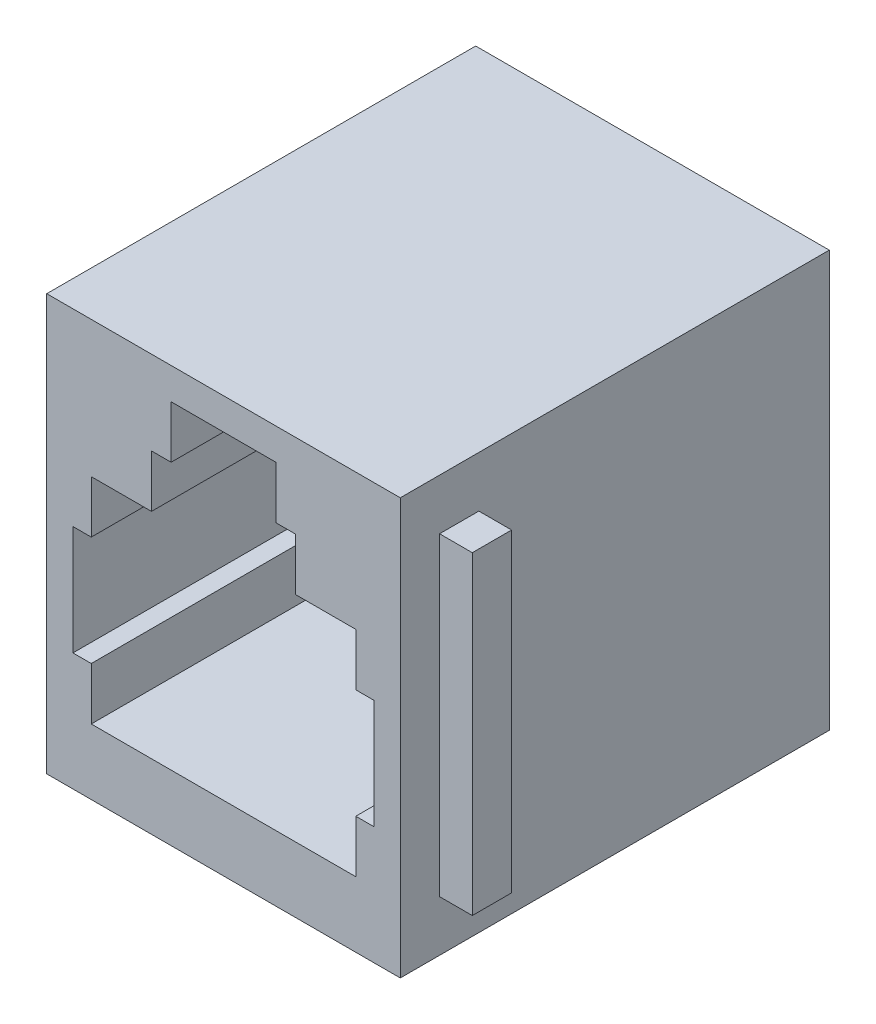
SolidWorks part; units mm, degrees
ref_plane "Front Plane" through (0, 0, 0) normal (0, 0, 1) x (1, 0, 0)
ref_plane "Top Plane" through (0, 0, 0) normal (0, 1, 0) x (1, 0, 0)
ref_plane "Right Plane" through (0, 0, 0) normal (1, 0, 0) x (0, 0, -1)
sketch "Sketch1" plane through (0, 0, 0) normal (0, 0, 1) x (1, 0, 0)
  line L0 (0, 0) -> (0, -7.94) construction
  line L1 (-6.75, 7.94) -> (6.75, 7.94)
  line L2 (-6.75, 7.94) -> (-6.75, -7.94)
  line L3 (-6.75, -7.94) -> (6.75, -7.94)
  line L4 (6.75, 7.94) -> (6.75, -7.94)
  line L5 (0, 0) -> (-6.75, 0) construction
  dimension "D1" = 15.88
  dimension "D2" = 13.5
extrude "Boss-Extrude1" add sketch "Sketch1" along normal blind 16.38
sketch "Sketch2" plane through (0, 0, 16.38) normal (0, 0, 1) x (1, 0, 0)
  line L0 (0, 0) -> (0, 6.74) construction
  line L1 (-2, 6.74) -> (2, 6.74)
  line L2 (2, 6.74) -> (2, 4.74)
  line L3 (2, 4.74) -> (2.75, 4.74)
  line L4 (2.75, 4.74) -> (2.75, 2.74)
  line L5 (2.75, 2.74) -> (5.05, 2.74)
  line L6 (5.05, 2.74) -> (5.05, 0.74)
  line L7 (5.05, 0.74) -> (5.75, 0.74)
  line L8 (5.75, 0.74) -> (5.75, -3.44)
  line L9 (5.75, -3.44) -> (5.05, -3.44)
  line L10 (5.05, -3.44) -> (5.05, -5.44)
  line L11 (5.05, -5.44) -> (-5.05, -5.44)
  line L12 (0, 0) -> (0, -5.44) construction
  line L13 (6.75, -7.94) -> (6.75, 7.94) construction
  line L14 (6.75, 7.94) -> (-6.75, 7.94) construction
  line L15 (-6.75, -7.94) -> (6.75, -7.94) construction
  line L16 (5.05, 0.74) -> (5.05, -3.44) construction
  line L17 (-5.05, -3.44) -> (-5.05, -5.44)
  line L18 (-5.75, -3.44) -> (-5.05, -3.44)
  line L19 (-5.05, 0.74) -> (-5.75, 0.74)
  line L20 (-5.75, 0.74) -> (-5.75, -3.44)
  line L21 (-5.05, 2.74) -> (-5.05, 0.74)
  line L22 (-2.75, 2.74) -> (-5.05, 2.74)
  line L23 (-2.75, 4.74) -> (-2.75, 2.74)
  line L24 (-2, 4.74) -> (-2.75, 4.74)
  line L25 (-2, 6.74) -> (-2, 4.74)
  point P8 (4.7, 1.6169)
  point P21 (4.7, 2.8427)
  point P22 (2.5785, 3.04)
  dimension "D1" = 1
  dimension "D2" = 1.2
  dimension "D3" = 2.5
  dimension "D4" = 2
  dimension "D5" = 0.7
  dimension "D6" = 2
  dimension "D7" = 4
  dimension "D8" = 5.5
extrude "Cut-Extrude1" cut sketch "Sketch2" against normal offset from surface (15.38 mm away) 1 up to face at (0, 0, 0)
sketch "Sketch3" plane through (0, 0, 0) normal (0, 1, 0) x (1, 0, 0)
  line L0 (0, 0) -> (0, -16.38) construction
  line L1 (6.75, -16.38) -> (-6.75, -16.38) construction
  line L2 (6.75, -16.38) -> (6.75, 0) construction
  line L3 (6.75, -13.38) -> (8, -13.38)
  line L4 (6.75, -13.38) -> (6.75, -14.88)
  line L5 (6.75, -14.88) -> (8, -14.88)
  line L6 (8, -13.38) -> (8, -14.88)
  line L7 (-8, -13.38) -> (-8, -14.88)
  line L8 (-6.75, -14.88) -> (-8, -14.88)
  line L9 (-6.75, -13.38) -> (-6.75, -14.88)
  line L10 (-6.75, -13.38) -> (-8, -13.38)
  dimension "D1" = 1.25
  dimension "D2" = 1.5
  dimension "D3" = 1.5
extrude "Boss-Extrude2" add sketch "Sketch3" along normal mid plane 12
